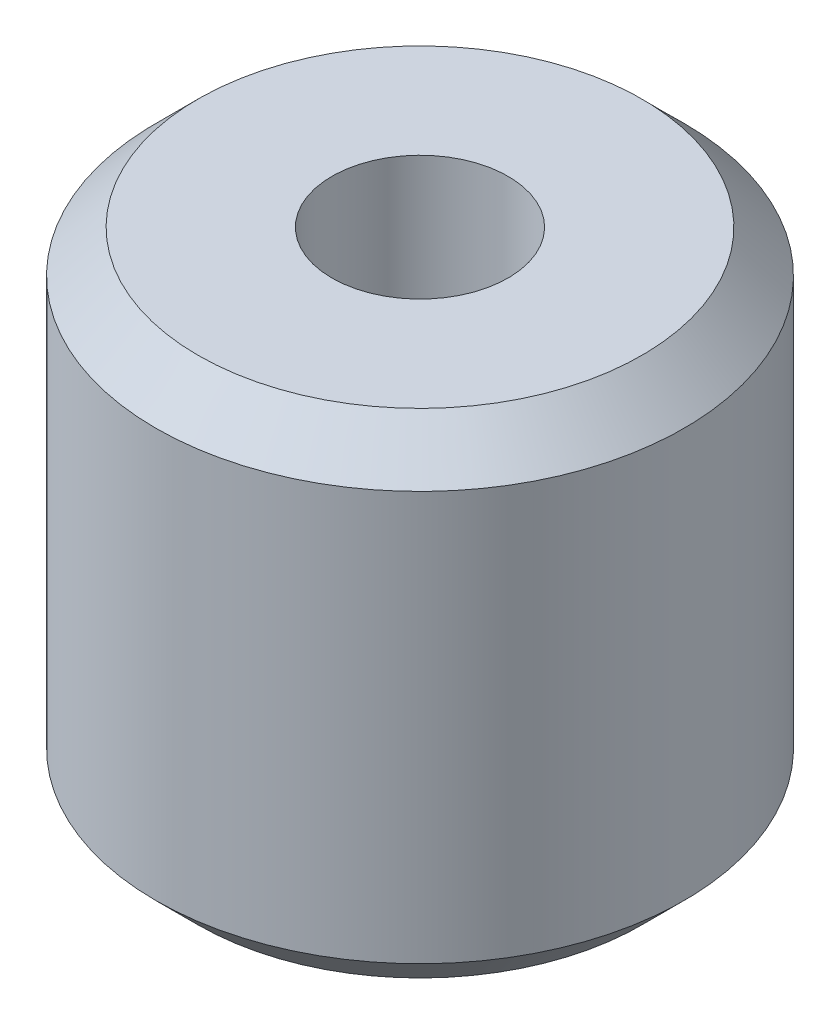
SolidWorks part; units mm, degrees
ref_plane "Front Plane" through (0, 0, 0) normal (0, 0, 1) x (1, 0, 0)
ref_plane "Top Plane" through (0, 0, 0) normal (0, 1, 0) x (1, 0, 0)
ref_plane "Right Plane" through (0, 0, 0) normal (1, 0, 0) x (0, 0, -1)
sketch "Sketch1" plane through (0, 0, 0) normal (0, 1, 0) x (1, 0, 0)
  circle A0 centre (0, 0) radius 1.59
  circle A1 centre (0, 0) radius 4.765
  dimension "D1" = 3.18
  dimension "D2" = 9.53
extrude "Boss-Extrude1" add sketch "Sketch1" along normal mid plane 8.9
chamfer "Chamfer1" distance 0.76 angle 45 2 edges at (0, -4.45, 4.765) (0, 4.45, 4.765)
